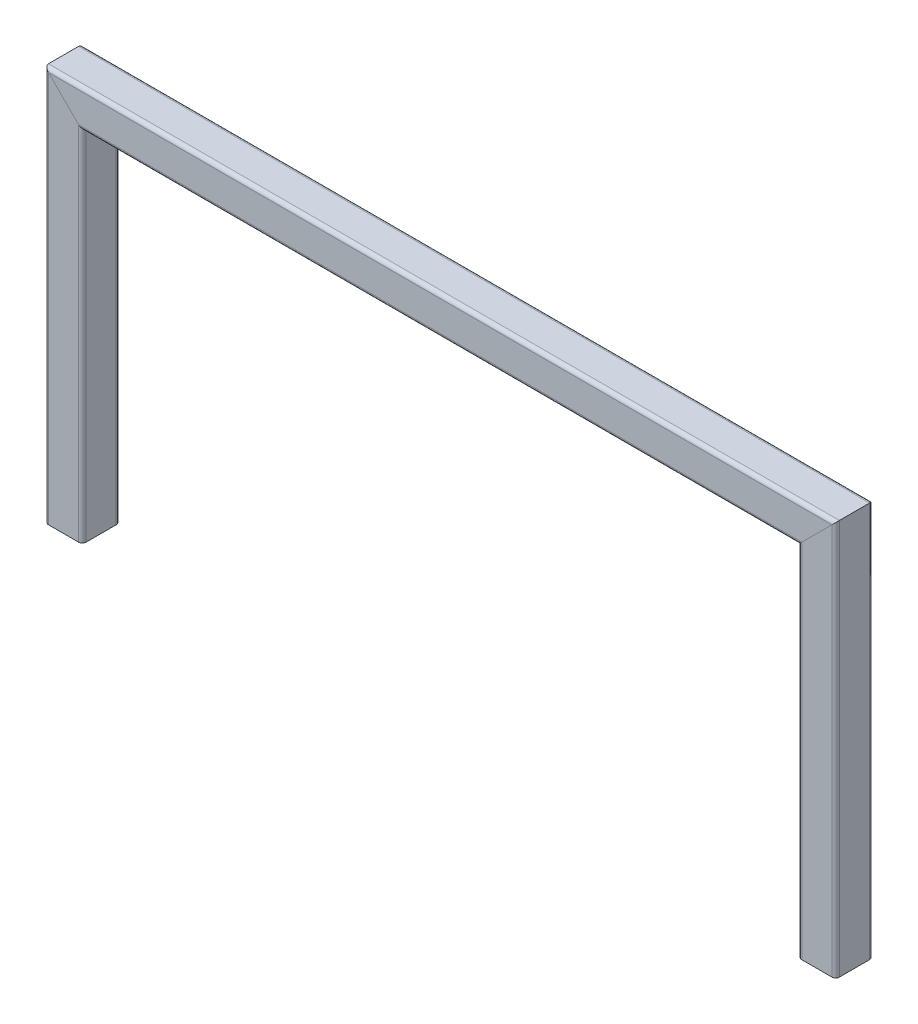
SolidWorks part; units mm, degrees
ref_plane "Plan de face" through (0, 0, 0) normal (0, 0, 1) x (1, 0, 0)
ref_plane "Plan de dessus" through (0, 0, 0) normal (0, 1, 0) x (1, 0, 0)
ref_plane "Plan de droite" through (0, 0, 0) normal (1, 0, 0) x (0, 0, -1)
sketch "Esquisse1" plane through (0, 0, 0) normal (0, 0, 1) x (1, 0, 0)
  line L0 (0, 0) -> (0, 300)
  line L1 (0, 300) -> (600, 300)
  line L2 (600, 300) -> (600, 0)
  dimension "D1" = 600
  dimension "D2" = 300
sketch "Esquisse2" plane through (0, 0, 0) normal (0, 1, 0) x (1, 0, 0)
  line L1 (-12, -15) -> (12, -15)
  line L2 (-15, -12) -> (-15, 12)
  line L3 (-12, 15) -> (12, 15)
  line L4 (15, -12) -> (15, 12)
  line L5 (-15, -15) -> (15, 15) construction
  line L6 (-15, 15) -> (15, -15) construction
  line L7 (-10, -13) -> (10, -13)
  line L8 (-13, -10) -> (-13, 10)
  line L9 (-10, 13) -> (10, 13)
  line L10 (13, -10) -> (13, 10)
  line L11 (-13, -13) -> (13, 13) construction
  line L12 (-13, 13) -> (13, -13) construction
  arc A0 (10, -13) -> (13, -10) centre (10, -10) ccw
  arc A1 (-13, 10) -> (-10, 13) centre (-10, 10) cw
  arc A2 (-10, -13) -> (-13, -10) centre (-10, -10) cw
  arc A3 (10, 13) -> (13, 10) centre (10, 10) cw
  arc A4 (12, -15) -> (15, -12) centre (12, -12) ccw
  arc A5 (-12, -15) -> (-15, -12) centre (-12, -12) cw
  arc A6 (12, 15) -> (15, 12) centre (12, 12) cw
  arc A7 (-15, 12) -> (-12, 15) centre (-12, 12) cw
  point P0 (0, 0)
  point P6 (0, 0)
  dimension "D5" = 3
  dimension "D1" = 30
  dimension "D2" = 30
  dimension "D3" = 26
  dimension "D4" = 26
sweep "Balayage1" add profiles "Esquisse2" path "Esquisse1"
